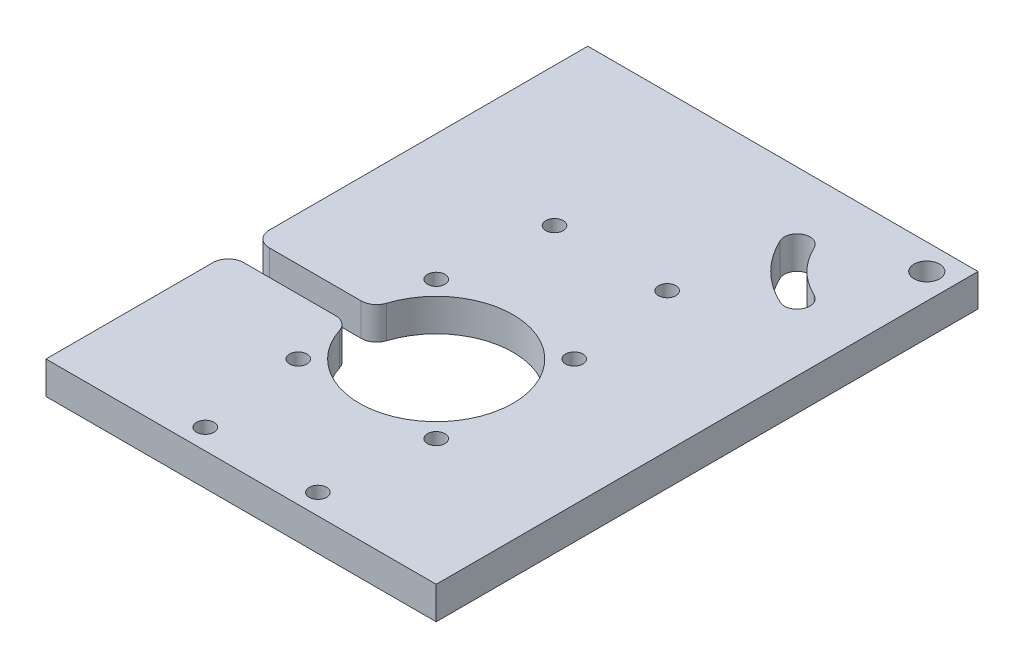
SolidWorks part; units mm, degrees
ref_plane "Front" through (0, 0, 0) normal (0, 0, 1) x (1, 0, 0)
ref_plane "Top" through (0, 0, 0) normal (0, 1, 0) x (1, 0, 0)
ref_plane "Right" through (0, 0, 0) normal (1, 0, 0) x (0, 0, -1)
sketch "Sketch1" plane through (0, 0, 0) normal (0, 1, 0) x (1, 0, 0)
  line L0 (-38.1, 0) -> (0, 0) construction
  line L1 (-38.1, 67.7) -> (38.1, 67.7)
  line L3 (-38.1, -38.1) -> (38.1, -38.1)
  line L4 (38.1, 67.7) -> (38.1, -38.1)
  line L5 (0, 0) -> (0, -38.1) construction
  line L6 (19.6296, 49.2296) -> (33.1, 62.7) construction
  line L11 (-38.1, 67.7) -> (-38.1, 2.5)
  line L12 (-38.1, 2.5) -> (-14.7902, 2.5)
  line L13 (-14.7902, -2.5) -> (-38.1, -2.5)
  line L14 (-38.1, -2.5) -> (-38.1, -38.1)
  circle A1 centre (0, 0) radius 28.575 construction
  circle A2 centre (33.1, 62.7) radius 2.5
  arc A3 (26.1057, 47.7006) -> (18.1006, 55.7057) centre (33.1, 62.7) cw
  arc A4 (23.9926, 43.1691) -> (13.5691, 53.5926) centre (33.1, 62.7) cw
  arc A5 (18.1006, 55.7057) -> (13.5691, 53.5926) centre (15.8348, 54.6491) ccw
  arc A6 (23.9926, 43.1691) -> (26.1057, 47.7006) centre (25.0491, 45.4348) ccw
  arc A7 (15.8348, 54.6491) -> (25.0491, 45.4348) centre (33.1, 62.7) ccw construction
  arc A8 (-14.7902, 2.5) -> (-14.7902, -2.5) centre (0, 0) cw
  point P9 (0, -38.1)
  point P12 (0, 0)
  point P20 (-38.1, 0)
  dimension "D3" = 57.15
  dimension "D6" = 5
  dimension "D9" = 45
  dimension "D12" = 15
  dimension "D2" = 76.2
  dimension "D4" = 67.7
  dimension "D5" = 19.05
  dimension "D7" = 5
  dimension "D8" = 5
  dimension "D10" = 40
  dimension "D11" = 5
extrude "Boss-Extrude1" add sketch "Sketch1" along normal blind 6.35
hole_wizard "M3 Clearance Hole1" positions "Sketch2" profile "Sketch4" hole size "M3" standard "ANSI Metric" end condition through all
sketch "Sketch2" plane through (0, 6.35, 0) normal (0, 1, 0) x (1, 0, 0)
  line L0 (0, 0) -> (13.4704, 13.4704) construction
  line L1 (-38.1, -38.1) -> (38.1, -38.1) construction
  point P0 (13.4704, 13.4704)
  dimension "D1" = 19.05
  dimension "D2" = 45
sketch "Sketch4" plane through (13.4704, 6.35, -13.4704) normal (1, 0, 0) x (0, 0, 1)
  line L0 (0, 0) -> (0, 6.35)
  line L1 (0, 6.35) -> (1.7, 6.35)
  line L2 (1.7, 6.35) -> (1.7, 0)
  line L5 (1.7, 0) -> (0, 0)
  line L11 (0, -6.35) -> (0, 107.95) construction
  dimension "Thru Hole Dia." = 3.4
  dimension "Thru Hole Depth" = 6.35
pattern_circular "CirPattern1" count 4 over 360 about axis through (0, 0, 0) along (0, 1, 0) of "M3 Clearance Hole1"
hole_wizard "M3 Clearance Hole3" positions "Sketch7" profile "Sketch8" hole size "M3" standard "ANSI Metric" end condition through all
sketch "Sketch7" plane through (0, 6.35, 0) normal (0, 1, 0) x (1, 0, 0)
  line L1 (-15, 38.1) -> (15, 38.1)
  line L2 (-15, 38.1) -> (-15, -38.1)
  line L3 (-15, -38.1) -> (15, -38.1)
  line L4 (15, 38.1) -> (15, -38.1)
  point P140 (15, 0)
  point P142 (0, 38.1)
  point P288 (-11, -34.1)
  point P290 (11, -34.1)
  point P292 (-11, 34.1)
  point P294 (11, 34.1)
  dimension "D1" = 30
  dimension "D2" = 76.2
  dimension "D3" = 4
  dimension "D4" = 4
  dimension "D5" = 4
  dimension "D6" = 4
sketch "Sketch8" plane through (11, 6.35, -34.1) normal (1, 0, 0) x (0, 0, 1)
  line L0 (0, 0) -> (0, 6.35)
  line L1 (0, 6.35) -> (1.7, 6.35)
  line L2 (1.7, 6.35) -> (1.7, 0)
  line L5 (1.7, 0) -> (0, 0)
  line L11 (0, -6.35) -> (0, 107.95) construction
  dimension "Thru Hole Dia." = 3.4
  dimension "Thru Hole Depth" = 6.35
fillet "Fillet1" radius 3 4 edges at (-38.1, 3.175, 2.5) (-38.1, 3.175, -2.5) (-14.7902, 3.175, 2.5) (-14.7902, 3.175, -2.5)
